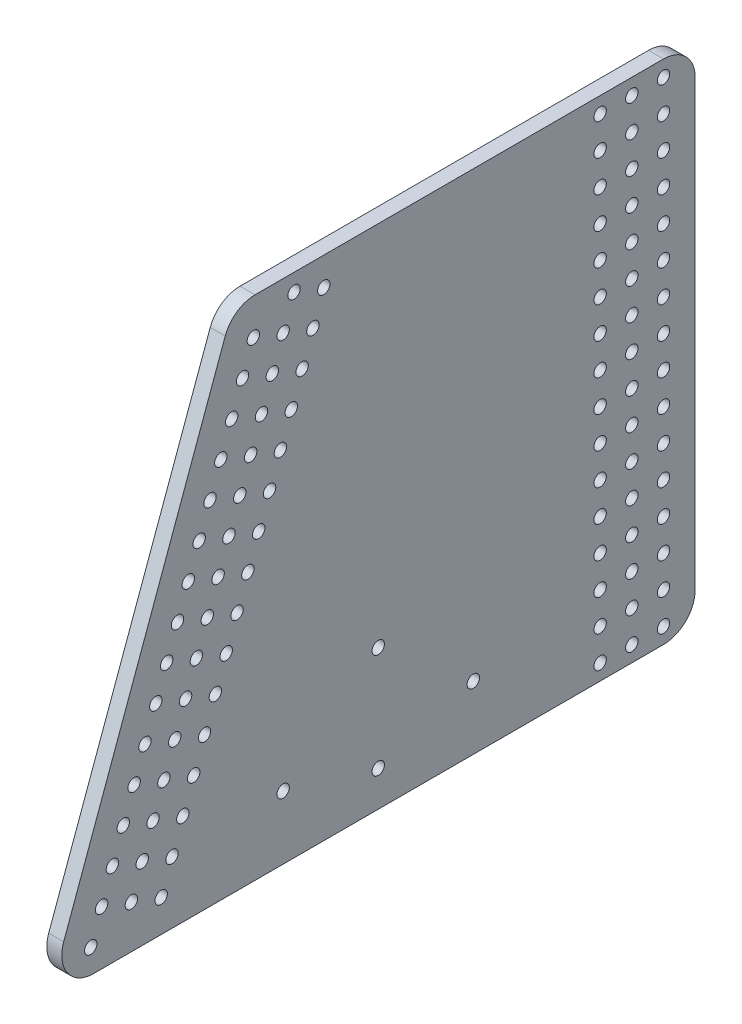
SolidWorks part; units mm, degrees
ref_plane "Front Plane" through (0, 0, 0) normal (0, 0, 1) x (1, 0, 0)
ref_plane "Top Plane" through (0, 0, 0) normal (0, 1, 0) x (1, 0, 0)
ref_plane "Right Plane" through (0, 0, 0) normal (1, 0, 0) x (0, 0, -1)
sketch "Sketch1" plane through (17.7134, 0, 0) normal (1, 0, 0) x (0, 0, -1)
  line L0 (0, 0) -> (259.2252, 0)
  line L1 (221.1252, 6.35) -> (221.1252, 19.05) construction
  line L2 (86.5421, 200.6401) -> (98.4762, 196.2965) construction
  line L3 (259.2252, 0) -> (259.2252, 203.2)
  line L4 (259.2252, 203.2) -> (73.9588, 203.2)
  line L5 (73.9588, 203.2) -> (0, 0)
  line L6 (98.4762, 196.2965) -> (110.4103, 191.9528) construction
  line L7 (82.1984, 188.706) -> (77.8548, 176.7719) construction
  line L8 (86.5421, 200.6401) -> (13.5151, 0) construction
  line L9 (98.4762, 196.2965) -> (27.0301, 0) construction
  line L13 (40.5452, 0) -> (110.4103, 191.9528) construction
  circle A0 centre (246.5252, 6.35) radius 2.4892
  circle A1 centre (233.8252, 6.35) radius 2.4892
  circle A2 centre (221.1252, 6.35) radius 2.4892
  circle A3 centre (221.1252, 19.05) radius 2.4892
  circle A4 centre (246.5252, 19.05) radius 2.4892
  circle A5 centre (233.8252, 19.05) radius 2.4892
  circle A6 centre (221.1252, 31.75) radius 2.4892
  circle A8 centre (98.4762, 196.2965) radius 2.4892
  circle A9 centre (110.4103, 191.9528) radius 2.4892
  circle A10 centre (246.5252, 31.75) radius 2.4892
  circle A11 centre (233.8252, 31.75) radius 2.4892
  circle A12 centre (221.1252, 44.45) radius 2.4892
  circle A13 centre (246.5252, 44.45) radius 2.4892
  circle A14 centre (233.8252, 44.45) radius 2.4892
  circle A15 centre (221.1252, 57.15) radius 2.4892
  circle A16 centre (246.5252, 57.15) radius 2.4892
  circle A17 centre (233.8252, 57.15) radius 2.4892
  circle A18 centre (221.1252, 69.85) radius 2.4892
  circle A19 centre (246.5252, 69.85) radius 2.4892
  circle A20 centre (233.8252, 69.85) radius 2.4892
  circle A21 centre (221.1252, 82.55) radius 2.4892
  circle A22 centre (246.5252, 82.55) radius 2.4892
  circle A23 centre (233.8252, 82.55) radius 2.4892
  circle A24 centre (221.1252, 95.25) radius 2.4892
  circle A25 centre (246.5252, 95.25) radius 2.4892
  circle A26 centre (233.8252, 95.25) radius 2.4892
  circle A27 centre (221.1252, 107.95) radius 2.4892
  circle A28 centre (246.5252, 107.95) radius 2.4892
  circle A29 centre (233.8252, 107.95) radius 2.4892
  circle A30 centre (221.1252, 120.65) radius 2.4892
  circle A31 centre (246.5252, 120.65) radius 2.4892
  circle A32 centre (233.8252, 120.65) radius 2.4892
  circle A33 centre (221.1252, 133.35) radius 2.4892
  circle A34 centre (246.5252, 133.35) radius 2.4892
  circle A35 centre (233.8252, 133.35) radius 2.4892
  circle A36 centre (221.1252, 146.05) radius 2.4892
  circle A37 centre (246.5252, 146.05) radius 2.4892
  circle A38 centre (233.8252, 146.05) radius 2.4892
  circle A39 centre (221.1252, 158.75) radius 2.4892
  circle A40 centre (246.5252, 158.75) radius 2.4892
  circle A41 centre (233.8252, 158.75) radius 2.4892
  circle A42 centre (221.1252, 171.45) radius 2.4892
  circle A43 centre (246.5252, 171.45) radius 2.4892
  circle A44 centre (233.8252, 171.45) radius 2.4892
  circle A45 centre (221.1252, 184.15) radius 2.4892
  circle A46 centre (246.5252, 184.15) radius 2.4892
  circle A47 centre (233.8252, 184.15) radius 2.4892
  circle A48 centre (221.1252, 196.85) radius 2.4892
  circle A49 centre (246.5252, 196.85) radius 2.4892
  circle A50 centre (233.8252, 196.85) radius 2.4892
  circle A51 centre (82.1984, 188.706) radius 2.4892
  circle A52 centre (77.8548, 176.7719) radius 2.4892
  circle A53 centre (94.1325, 184.3624) radius 2.4892
  circle A54 centre (106.0666, 180.0187) radius 2.4892
  circle A55 centre (73.5111, 164.8378) radius 2.4892
  circle A56 centre (89.7889, 172.4283) radius 2.4892
  circle A57 centre (101.723, 168.0846) radius 2.4892
  circle A58 centre (69.1675, 152.9037) radius 2.4892
  circle A59 centre (85.4452, 160.4942) radius 2.4892
  circle A60 centre (97.3793, 156.1505) radius 2.4892
  circle A61 centre (64.8238, 140.9696) radius 2.4892
  circle A62 centre (81.1016, 148.5601) radius 2.4892
  circle A63 centre (93.0357, 144.2164) radius 2.4892
  circle A64 centre (60.4802, 129.0355) radius 2.4892
  circle A65 centre (76.7579, 136.626) radius 2.4892
  circle A66 centre (88.692, 132.2823) radius 2.4892
  circle A67 centre (56.1365, 117.1014) radius 2.4892
  circle A68 centre (72.4142, 124.6919) radius 2.4892
  circle A69 centre (84.3483, 120.3482) radius 2.4892
  circle A70 centre (51.7928, 105.1673) radius 2.4892
  circle A71 centre (68.0706, 112.7578) radius 2.4892
  circle A72 centre (80.0047, 108.4141) radius 2.4892
  circle A73 centre (47.4492, 93.2332) radius 2.4892
  circle A74 centre (63.7269, 100.8237) radius 2.4892
  circle A75 centre (75.661, 96.48) radius 2.4892
  circle A76 centre (43.1055, 81.2992) radius 2.4892
  circle A77 centre (59.3833, 88.8896) radius 2.4892
  circle A78 centre (71.3174, 84.5459) radius 2.4892
  circle A79 centre (38.7619, 69.3651) radius 2.4892
  circle A80 centre (55.0396, 76.9555) radius 2.4892
  circle A81 centre (66.9737, 72.6118) radius 2.4892
  circle A82 centre (34.4182, 57.431) radius 2.4892
  circle A83 centre (50.696, 65.0214) radius 2.4892
  circle A84 centre (62.6301, 60.6777) radius 2.4892
  circle A85 centre (30.0746, 45.4969) radius 2.4892
  circle A86 centre (46.3523, 53.0873) radius 2.4892
  circle A87 centre (58.2864, 48.7436) radius 2.4892
  circle A88 centre (25.7309, 33.5628) radius 2.4892
  circle A89 centre (42.0087, 41.1532) radius 2.4892
  circle A90 centre (53.9428, 36.8095) radius 2.4892
  circle A91 centre (21.3872, 21.6287) radius 2.4892
  circle A92 centre (37.665, 29.2191) radius 2.4892
  circle A93 centre (49.5991, 24.8755) radius 2.4892
  circle A94 centre (17.0436, 9.6946) radius 2.4892
  circle A95 centre (33.3213, 17.285) radius 2.4892
  circle A96 centre (45.2554, 12.9414) radius 2.4892
  dimension "D8" = 12.7
  dimension "D2" = 259.2252
  dimension "D4" = 12.7
  dimension "D10" = 12.7
  dimension "D11" = 12.7
  dimension "D7" = 12.7
  dimension "D14" = 11.2472
  dimension "D15" = 16
  dimension "D16" = 4.9784
  dimension "D1" = 203.2
  dimension "D5" = 12.7
  dimension "D9" = 185.2664
  dimension "D3" = 12.7
  dimension "D6" = 6.35
  dimension "D13" = 12.7
  dimension "D17" = 12.7
  dimension "D12" = 16
extrude "Boss-Extrude1" add sketch "Sketch1" along normal blind 6
fillet "Fillet1" radius 12.7 4 edges at (20.7134, 203.2, -259.2252) (20.7134, 0, -259.2252) (20.7134, 203.2, -73.9588) (20.7134, 0, 0)
sketch "Sketch4" plane through (17.7134, 0, 0) normal (-1, 0, 0) x (0, 0, 1)
  line L0 (-246.5252, 203.2) -> (-82.8514, 203.2) construction
  line L1 (-183.0252, 190.5) -> (-170.3252, 190.5) construction
  line L2 (-183.0252, 190.5) -> (-183.0252, 76.2) construction
  line L3 (-198.9002, 107.95) -> (-198.9002, 158.75) construction
  circle A0 centre (-183.0252, 190.5) radius 3.0309
  circle A2 centre (-170.3252, 190.5) radius 3.0309
  circle A3 centre (-157.6252, 190.5) radius 3.0309
  circle A4 centre (-144.9252, 190.5) radius 3.0309
  circle A5 centre (-183.0252, 76.2) radius 3.0309
  circle A6 centre (-170.3252, 76.2) radius 3.0309
  circle A7 centre (-157.6252, 76.2) radius 3.0309
  circle A8 centre (-144.9252, 76.2) radius 3.0309
  circle A9 centre (-132.2252, 190.5) radius 3.0309
  circle A10 centre (-132.2252, 76.2) radius 3.0309
  circle A11 centre (-221.1252, 184.15) radius 2.4892 construction
  circle A12 centre (-198.9002, 158.75) radius 3.0309
  circle A13 centre (-198.9002, 107.95) radius 3.0309
  circle A14 centre (-116.3502, 158.75) radius 3.0309
  circle A15 centre (-116.3502, 107.95) radius 3.0309
  point P34 (-198.9002, 133.35)
  dimension "D1" = 12.7
  dimension "D2" = 6.0617
  dimension "D3" = 5
  dimension "D6" = 38.1
  dimension "D8" = 50.8
  dimension "D9" = 82.55
  dimension "D10" = 15.875
  dimension "D11" = 57.15
  dimension "D4" = 12.7
  dimension "D7" = 114.3
  dimension "D5" = 2
extrude "Cut-Extrude1" cut sketch "Sketch4" against normal blind 3.175
sketch "Sketch5" plane through (17.7134, 0, 0) normal (-1, 0, 0) x (0, 0, 1)
  line L0 (-170.3252, 25.4) -> (-94.1252, 25.4) construction
  line L2 (-259.2252, 12.7) -> (-259.2252, 190.5) construction
  line L3 (-18.1375, 0) -> (-246.5252, 0) construction
  circle A0 centre (-170.3252, 25.4) radius 2.4892
  circle A1 centre (-94.1252, 25.4) radius 2.4892
  circle A2 centre (-132.2252, 56.134) radius 2.4892
  circle A3 centre (-132.2252, 14.224) radius 2.4892
  point P12 (-132.542, 52.324)
  point P13 (0, 0)
  dimension "D1" = 76.2
  dimension "D2" = 4.9784
  dimension "D5" = 38.1
  dimension "D7" = 30.734
  dimension "D3" = 88.9
  dimension "D4" = 25.4
  dimension "D6" = 11.176
extrude "Cut-Extrude2" cut sketch "Sketch5" against normal through all
sketch "Sketch6" plane through (23.7134, 0, 0) normal (1, 0, 0) x (0, 0, -1)
  line L0 (259.2252, -983.9832) -> (259.2252, 49016.0168) construction
  line L2 (-782.2087, 0) -> (49217.7913, 0) construction
  line L3 (259.2252, 12.7) -> (259.2252, 190.5) construction
  line L4 (18.1375, 0) -> (246.5252, 0) construction
  point P3 (259.2252, 0)
  point P5 (0, 0)
